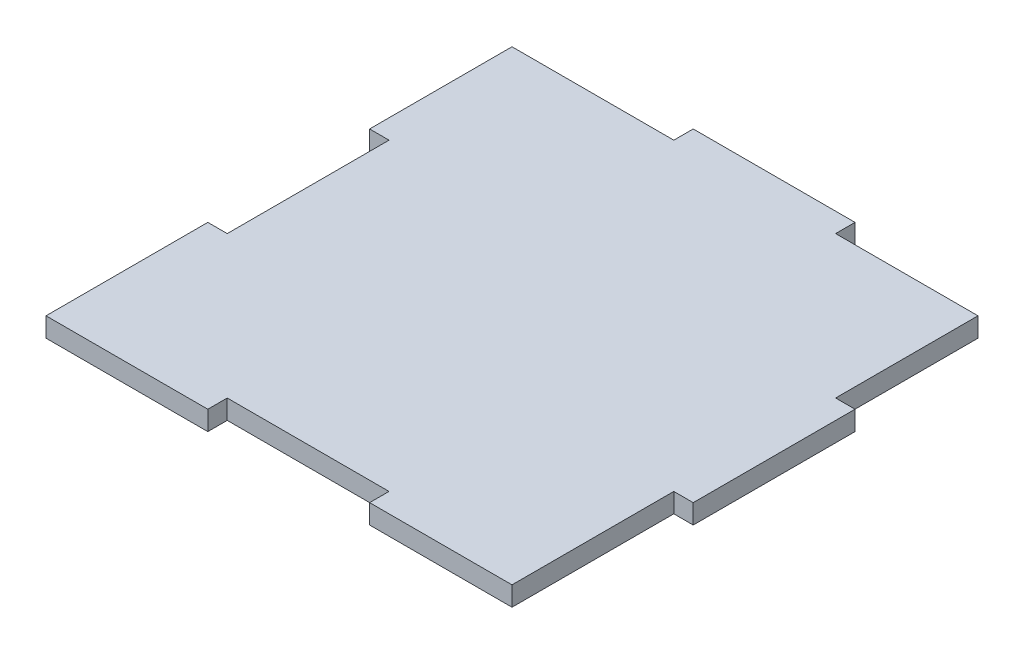
SolidWorks part; units mm, degrees
ref_plane "Front Plane" through (0, 0, 0) normal (0, 0, 1) x (1, 0, 0)
ref_plane "Top Plane" through (0, 0, 0) normal (0, 1, 0) x (1, 0, 0)
ref_plane "Right Plane" through (0, 0, 0) normal (1, 0, 0) x (0, 0, -1)
sketch "Sketch1" plane through (0, 0, 0) normal (0, 1, 0) x (1, 0, 0)
  line L0 (-72, 28) -> (-66, 28)
  line L1 (-72, -72) -> (72, -72)
  line L2 (-72, -72) -> (-72, 72)
  line L3 (-72, 72) -> (72, 72)
  line L4 (72, -72) -> (72, 72)
  line L5 (-72, -72) -> (72, 72) construction
  line L6 (-72, 72) -> (72, -72) construction
  line L7 (-66, 28) -> (-66, -22)
  line L8 (28, -72) -> (28, -66)
  line L9 (-22, 72) -> (-22, 78)
  line L10 (-22, 78) -> (28, 78)
  line L11 (28, 72) -> (28, 78)
  line L12 (72, 28) -> (78, 28)
  line L13 (78, 28) -> (78, -22)
  line L14 (-22, -72) -> (-22, -66)
  line L15 (-22, -66) -> (28, -66)
  line L16 (3, 78) -> (3, -72) construction
  line L17 (-72, 3) -> (78, 3) construction
  line L18 (72, -22) -> (78, -22)
  line L19 (-72, -22) -> (-66, -22)
  point P0 (0, 0)
  point P14 (5.0408, 78)
  point P16 (5.2223, -72)
  point P22 (3, 3)
  point P23 (15.6845, 3)
  point P24 (0, 0)
  point P25 (-72, -2.9655)
  point P26 (5.4038, 78)
  point P27 (3, 3)
  point P28 (5.5852, 78)
  point P29 (6.8556, 78)
  point P30 (78, 3.5675)
  point P31 (-72, -11.6762)
  point P32 (4.958, -72)
  point P33 (0, 0)
  point P34 (0, 0)
  point P35 (3, -66)
  point P36 (0, 0)
  point P37 (0, 0)
  point P40 (3, -66)
  point P45 (-66, 3)
  point P46 (72, 28)
  point P47 (3, 3)
  point P48 (0, 0)
  dimension "D1" = 144
  dimension "D2" = 25
  dimension "D3" = 6
extrude "Boss-Extrude1" add sketch "Sketch1" along normal blind 6 contours L19 L2 L1 L14 L15 L8 L4 L3 L0 L7 | L3 L11 L10 L9 | L4 L18 L13 L12
